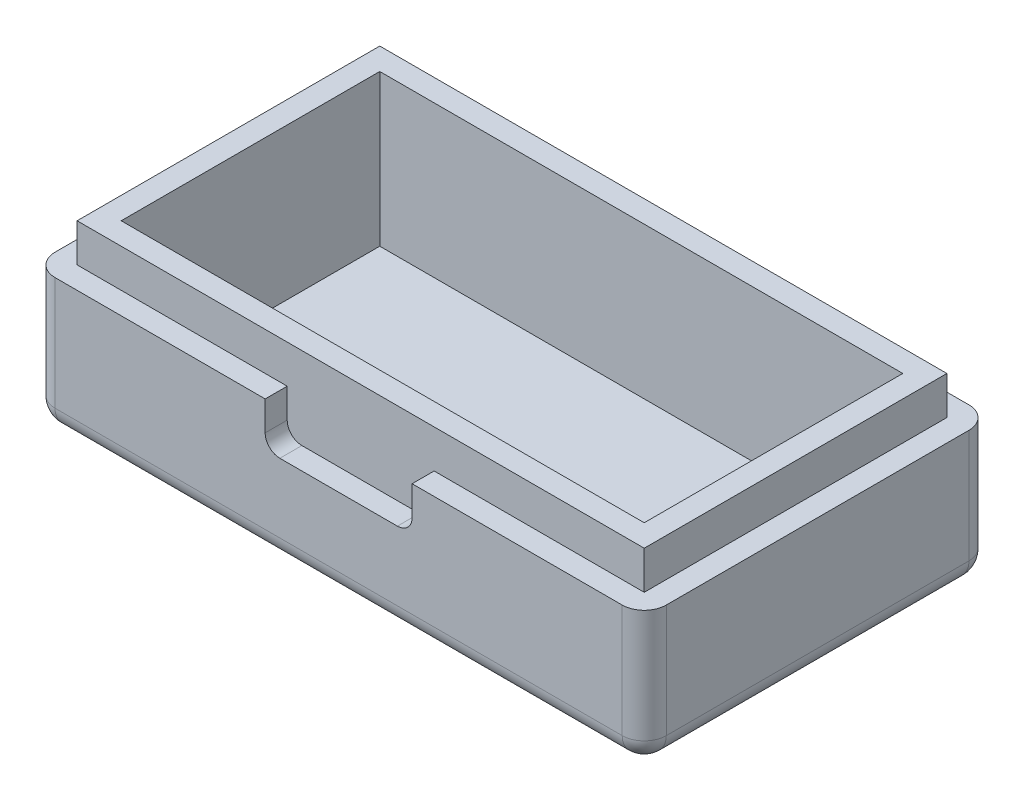
SolidWorks part; units mm, degrees
ref_plane "Front Plane" through (0, 0, 0) normal (0, 0, 1) x (1, 0, 0)
ref_plane "Top Plane" through (0, 0, 0) normal (0, 1, 0) x (1, 0, 0)
ref_plane "Right Plane" through (0, 0, 0) normal (1, 0, 0) x (0, 0, -1)
sketch "Sketch1" plane through (0, 0, 0) normal (0, 1, 0) x (1, 0, 0)
  line L1 (0, 0) -> (41.6, 0)
  line L2 (0, 0) -> (0, 23.6)
  line L3 (0, 23.6) -> (41.6, 23.6)
  line L4 (41.6, 0) -> (41.6, 23.6)
  dimension "D1" = 41.6
  dimension "D2" = 23.6
extrude "Boss-Extrude1" add sketch "Sketch1" along normal blind 11.8
sketch "Sketch2" plane through (0, 11.8, 0) normal (0, 1, 0) x (1, 0, 0)
  line L0 (20.8, 23.6) -> (20.8, 0) construction
  line L1 (41.6, 23.6) -> (0, 23.6) construction
  line L2 (0, 0) -> (41.6, 0) construction
  line L4 (3, 3) -> (38.6, 3)
  line L5 (3, 3) -> (3, 20.6)
  line L6 (3, 20.6) -> (38.6, 20.6)
  line L7 (38.6, 3) -> (38.6, 20.6)
  line L8 (3, 3) -> (38.6, 20.6) construction
  line L9 (3, 20.6) -> (38.6, 3) construction
  point P6 (20.8, 11.8)
  dimension "D1" = 17.6
  dimension "D2" = 35.6
extrude "Cut-Extrude1" cut sketch "Sketch2" against normal blind 10.3
sketch "Sketch4" plane through (0, 11.8, 0) normal (0, 1, 0) x (1, 0, 0)
  line L1 (0, 23.6) -> (41.6, 23.6)
  line L2 (0, 23.6) -> (0, 0)
  line L3 (0, 0) -> (41.6, 0)
  line L4 (41.6, 23.6) -> (41.6, 0)
  line L5 (1.5, 22.1) -> (40.1, 22.1)
  line L6 (1.5, 22.1) -> (1.5, 1.5)
  line L7 (1.5, 1.5) -> (40.1, 1.5)
  line L8 (40.1, 22.1) -> (40.1, 1.5)
  dimension "D1" = 1.5
  dimension "D2" = 1.5
  dimension "D3" = 1.5
  dimension "D4" = 1.5
extrude "Cut-Extrude2" cut sketch "Sketch4" against normal blind 2.6
fillet "Fillet1" radius 1.5 8 edges at (0, 4.6, 0) (0, 0, -11.8) (0, 4.6, -23.6) (41.6, 0, -11.8) (20.8, 0, -23.6) (20.8, 0, 0) (41.6, 4.6, -23.6) (41.6, 4.6, 0)
sketch "Sketch5" plane through (0, 0, -23.6) normal (0, 0, -1) x (-1, 0, 0)
  line L0 (-20.8, 6.2) -> (-20.8, 1.5) construction
  line L1 (-25.8, 9.2) -> (-15.8, 9.2)
  line L2 (-25.8, 9.2) -> (-25.8, 7.2)
  line L3 (-24.8, 6.2) -> (-16.8, 6.2)
  line L4 (-15.8, 9.2) -> (-15.8, 7.2)
  line L5 (-40.1, 1.5) -> (-1.5, 1.5) construction
  line L6 (-40.1, 9.2) -> (-1.5, 9.2) construction
  arc A0 (-16.8, 6.2) -> (-15.8, 7.2) centre (-16.8, 7.2) ccw
  arc A1 (-25.8, 7.2) -> (-24.8, 6.2) centre (-24.8, 7.2) ccw
  point P12 (-15.8, 6.2)
  dimension "D3" = 1
  dimension "D1" = 10
  dimension "D2" = 3
extrude "Cut-Extrude3" cut sketch "Sketch5" against normal up to surface (1.5 mm away) up to face at (20.8, 10.5, -22.1)
sketch "Sketch6" plane through (0, 0, 0) normal (0, 0, 1) x (1, 0, 0)
  line L0 (25.8, 9.2) -> (25.8, 7.2) construction
  line L1 (15.8, 9.2) -> (25.8, 9.2)
  line L2 (15.8, 9.2) -> (15.8, 7.2)
  line L3 (16.8, 6.2) -> (24.8, 6.2)
  line L4 (25.8, 9.2) -> (25.8, 7.2)
  line L5 (24.8, 6.2) -> (16.8, 6.2) construction
  arc A0 (24.8, 6.2) -> (25.8, 7.2) centre (24.8, 7.2) ccw
  arc A1 (15.8, 7.2) -> (16.8, 6.2) centre (16.8, 7.2) ccw
  point P11 (25.8, 6.2)
  dimension "D1" = 1
extrude "Cut-Extrude4" cut sketch "Sketch6" against normal up to surface (1.5 mm away) up to face at (20.8, 10.5, -1.5)
